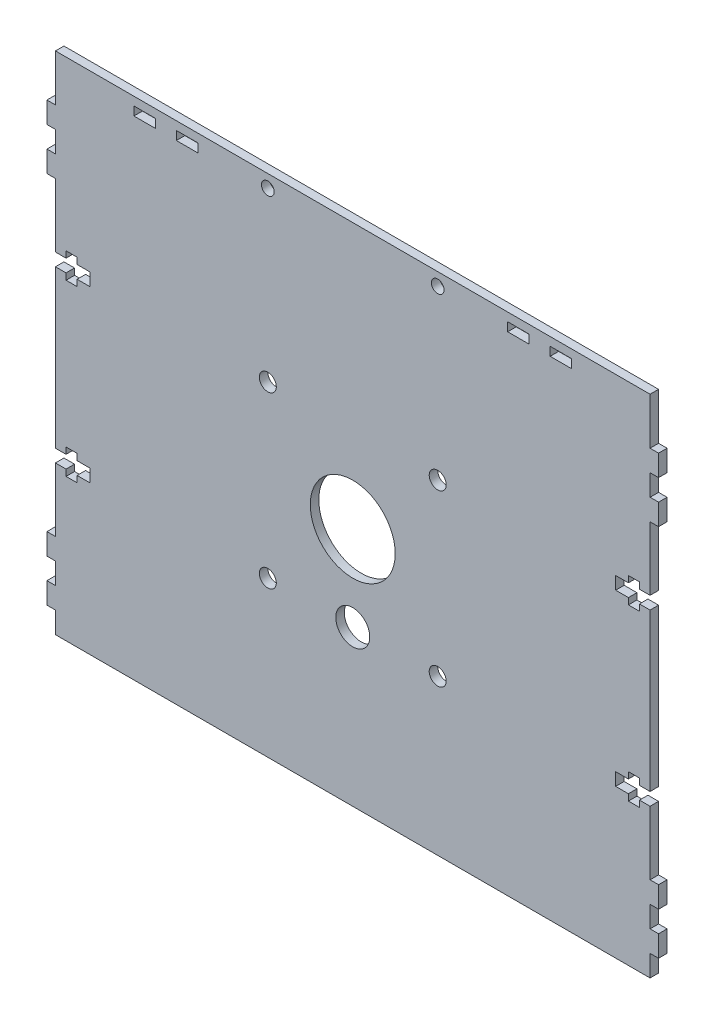
SolidWorks part; units mm, degrees
ref_plane "前视基准面" through (0, 0, 0) normal (0, 0, 1) x (1, 0, 0)
ref_plane "上视基准面" through (0, 0, 0) normal (0, 1, 0) x (1, 0, 0)
ref_plane "右视基准面" through (0, 0, 0) normal (1, 0, 0) x (0, 0, -1)
sketch "草图1" plane through (0, 0, 0) normal (0, 0, 1) x (1, 0, 0)
  line L50 (249.9534, 275.9629) -> (249.9534, 255.9629) construction
  line L53 (317.4534, 257.4629) -> (317.4534, 258.9629)
  line L54 (317.4534, 254.4629) -> (317.4534, 252.9629)
  line L55 (319.9534, 254.4629) -> (317.4534, 254.4629)
  line L56 (317.4534, 258.9629) -> (314.8534, 258.9629)
  line L57 (314.8534, 258.9629) -> (314.8534, 257.4629)
  line L58 (314.8534, 257.4629) -> (311.8534, 257.4629)
  line L59 (311.8534, 254.4629) -> (311.8534, 257.4629)
  line L60 (314.8534, 254.4629) -> (311.8534, 254.4629)
  line L61 (314.8534, 252.9629) -> (314.8534, 254.4629)
  line L62 (317.4534, 252.9629) -> (314.8534, 252.9629)
  line L63 (317.4534, 257.4629) -> (319.9534, 257.4629)
  line L68 (319.9534, 254.4629) -> (319.9534, 257.4629) construction
  line L69 (311.8534, 255.9629) -> (319.9534, 255.9629) construction
  line L73 (311.8534, 295.9629) -> (319.9534, 295.9629) construction
  line L75 (317.4534, 294.4629) -> (319.9534, 294.4629)
  line L76 (317.4534, 298.9629) -> (314.8534, 298.9629)
  line L77 (314.8534, 298.9629) -> (314.8534, 297.4629)
  line L78 (314.8534, 297.4629) -> (311.8534, 297.4629)
  line L79 (311.8534, 297.4629) -> (311.8534, 294.4629)
  line L80 (314.8534, 294.4629) -> (311.8534, 294.4629)
  line L81 (314.8534, 292.9629) -> (314.8534, 294.4629)
  line L82 (317.4534, 292.9629) -> (314.8534, 292.9629)
  line L83 (319.9534, 297.4629) -> (317.4534, 297.4629)
  line L84 (317.4534, 297.4629) -> (317.4534, 298.9629)
  line L85 (317.4534, 294.4629) -> (317.4534, 292.9629)
  line L111 (182.4534, 294.4629) -> (182.4534, 292.9629)
  line L112 (182.4534, 297.4629) -> (182.4534, 298.9629)
  line L113 (179.9534, 297.4629) -> (182.4534, 297.4629)
  line L114 (182.4534, 292.9629) -> (185.0534, 292.9629)
  line L115 (185.0534, 292.9629) -> (185.0534, 294.4629)
  line L116 (185.0534, 294.4629) -> (188.0534, 294.4629)
  line L117 (188.0534, 297.4629) -> (188.0534, 294.4629)
  line L118 (185.0534, 297.4629) -> (188.0534, 297.4629)
  line L119 (185.0534, 298.9629) -> (185.0534, 297.4629)
  line L120 (182.4534, 298.9629) -> (185.0534, 298.9629)
  line L121 (182.4534, 294.4629) -> (179.9534, 294.4629)
  line L122 (182.4534, 257.4629) -> (179.9534, 257.4629)
  line L123 (182.4534, 252.9629) -> (185.0534, 252.9629)
  line L124 (185.0534, 252.9629) -> (185.0534, 254.4629)
  line L125 (185.0534, 254.4629) -> (188.0534, 254.4629)
  line L126 (188.0534, 254.4629) -> (188.0534, 257.4629)
  line L127 (185.0534, 257.4629) -> (188.0534, 257.4629)
  line L128 (185.0534, 258.9629) -> (185.0534, 257.4629)
  line L129 (182.4534, 258.9629) -> (185.0534, 258.9629)
  line L130 (179.9534, 254.4629) -> (182.4534, 254.4629)
  line L131 (182.4534, 254.4629) -> (182.4534, 252.9629)
  line L132 (182.4534, 257.4629) -> (182.4534, 258.9629)
  line L133 (179.9534, 297.4629) -> (179.9534, 294.4629) construction
  line L134 (188.0534, 295.9629) -> (179.9534, 295.9629) construction
  line L135 (188.0534, 255.9629) -> (179.9534, 255.9629) construction
  line L163 (179.9534, 294.4629) -> (179.9534, 257.4629)
  line L172 (319.9534, 257.4629) -> (319.9534, 294.4629)
  line L188 (179.9534, 239.4629) -> (177.9534, 239.4629)
  line L189 (177.9534, 239.4629) -> (177.9534, 234.4629)
  line L190 (177.9534, 234.4629) -> (179.9534, 234.4629)
  line L191 (179.9534, 234.4629) -> (179.9534, 229.4629)
  line L192 (179.9534, 229.4629) -> (177.9534, 229.4629)
  line L193 (177.9534, 229.4629) -> (177.9534, 224.4629)
  line L194 (177.9534, 224.4629) -> (179.9534, 224.4629)
  line L196 (179.9534, 327.4629) -> (179.9534, 345.9629) construction
  line L197 (177.9534, 327.4629) -> (179.9534, 327.4629)
  line L198 (177.9534, 322.4629) -> (177.9534, 327.4629)
  line L199 (179.9534, 322.4629) -> (177.9534, 322.4629)
  line L200 (179.9534, 317.4629) -> (179.9534, 322.4629)
  line L201 (177.9534, 317.4629) -> (179.9534, 317.4629)
  line L202 (177.9534, 312.4629) -> (177.9534, 317.4629)
  line L203 (179.9534, 312.4629) -> (177.9534, 312.4629)
  line L224 (319.9534, 312.4629) -> (321.9534, 312.4629)
  line L225 (321.9534, 312.4629) -> (321.9534, 317.4629)
  line L226 (321.9534, 317.4629) -> (319.9534, 317.4629)
  line L227 (319.9534, 317.4629) -> (319.9534, 322.4629)
  line L228 (319.9534, 322.4629) -> (321.9534, 322.4629)
  line L229 (321.9534, 322.4629) -> (321.9534, 327.4629)
  line L230 (321.9534, 327.4629) -> (319.9534, 327.4629)
  line L233 (321.9534, 224.4629) -> (319.9534, 224.4629)
  line L234 (321.9534, 229.4629) -> (321.9534, 224.4629)
  line L235 (319.9534, 229.4629) -> (321.9534, 229.4629)
  line L236 (319.9534, 234.4629) -> (319.9534, 229.4629)
  line L237 (321.9534, 234.4629) -> (319.9534, 234.4629)
  line L238 (321.9534, 239.4629) -> (321.9534, 234.4629)
  line L239 (319.9534, 239.4629) -> (321.9534, 239.4629)
  line L261 (249.9534, 255.9629) -> (229.9534, 255.9629) construction
  line L262 (319.9534, 327.4629) -> (319.9534, 330.9829)
  line L268 (179.9534, 297.4629) -> (179.9534, 312.4629)
  line L271 (319.9534, 312.4629) -> (319.9534, 297.4629)
  line L272 (319.9534, 254.4629) -> (319.9534, 239.4629)
  line L275 (179.9534, 239.4629) -> (179.9534, 254.4629)
  line L279 (317.4534, 330.9829) -> (317.4534, 345.9629) construction
  line L280 (317.4534, 345.9629) -> (179.9534, 345.9629) construction
  line L285 (317.4534, 338.4729) -> (179.9534, 338.4729)
  line L286 (179.9534, 327.4629) -> (179.9534, 338.4729)
  line L288 (317.4534, 338.4729) -> (319.9534, 338.4729)
  line L289 (319.9534, 338.4729) -> (319.9534, 330.9829)
  line L290 (319.9534, 219.4409) -> (179.9534, 219.4409)
  line L291 (179.9534, 219.4409) -> (179.9534, 224.4629)
  line L292 (319.9534, 219.4409) -> (319.9534, 224.4629)
  line L310 (203.4784, 334.4379) -> (198.4284, 336.4879) construction
  line L311 (286.4284, 336.4879) -> (291.4784, 336.4879)
  line L312 (286.4284, 336.4879) -> (286.4284, 334.4379)
  line L313 (286.4284, 334.4379) -> (291.4784, 334.4379)
  line L314 (291.4784, 336.4879) -> (291.4784, 334.4379)
  line L315 (286.4284, 336.4879) -> (291.4784, 334.4379) construction
  line L316 (286.4284, 334.4379) -> (291.4784, 336.4879) construction
  line L317 (296.4284, 336.4879) -> (301.4784, 336.4879)
  line L318 (296.4284, 336.4879) -> (296.4284, 334.4379)
  line L319 (296.4284, 334.4379) -> (301.4784, 334.4379)
  line L320 (301.4784, 336.4879) -> (301.4784, 334.4379)
  line L321 (296.4284, 336.4879) -> (301.4784, 334.4379) construction
  line L322 (296.4284, 334.4379) -> (301.4784, 336.4879) construction
  line L323 (268.4534, 343.4629) -> (266.9534, 343.4629) [skipped]
  line L324 (271.4534, 343.4629) -> (272.9534, 343.4629) [skipped]
  line L325 (271.4534, 345.9629) -> (271.4534, 343.4629) [skipped]
  line L326 (266.9534, 343.4629) -> (266.9534, 340.8629) [skipped]
  line L327 (266.9534, 340.8629) -> (268.4534, 340.8629) [skipped]
  line L328 (268.4534, 340.8629) -> (268.4534, 337.8629) [skipped]
  line L329 (271.4534, 340.8629) -> (271.4534, 337.8629) [skipped]
  line L330 (272.9534, 340.8629) -> (271.4534, 340.8629) [skipped]
  line L331 (272.9534, 343.4629) -> (272.9534, 340.8629) [skipped]
  line L332 (268.4534, 343.4629) -> (268.4534, 345.9629) [skipped]
  line L333 (231.4534, 343.4629) -> (231.4534, 345.9629) [skipped]
  line L334 (226.9534, 343.4629) -> (226.9534, 340.8629) [skipped]
  line L335 (226.9534, 340.8629) -> (228.4534, 340.8629) [skipped]
  line L336 (228.4534, 340.8629) -> (228.4534, 337.8629) [skipped]
  line L337 (231.4534, 340.8629) -> (231.4534, 337.8629) [skipped]
  line L338 (232.9534, 340.8629) -> (231.4534, 340.8629) [skipped]
  line L339 (232.9534, 343.4629) -> (232.9534, 340.8629) [skipped]
  line L340 (228.4534, 345.9629) -> (228.4534, 343.4629) [skipped]
  line L341 (228.4534, 343.4629) -> (226.9534, 343.4629) [skipped]
  line L342 (231.4534, 343.4629) -> (232.9534, 343.4629) [skipped]
  line L343 (268.4534, 345.9629) -> (231.4534, 345.9629) [skipped]
  line L344 (213.4534, 345.9629) -> (213.4534, 347.9629) [skipped]
  line L345 (213.4534, 347.9629) -> (208.4534, 347.9629) [skipped]
  line L346 (208.4534, 347.9629) -> (208.4534, 345.9629) [skipped]
  line L347 (208.4534, 345.9629) -> (203.4534, 345.9629) [skipped]
  line L348 (203.4534, 345.9629) -> (203.4534, 347.9629) [skipped]
  line L349 (203.4534, 347.9629) -> (198.4534, 347.9629) [skipped]
  line L350 (198.4534, 347.9629) -> (198.4534, 345.9629) [skipped]
  line L352 (301.4534, 345.9629) -> (319.9534, 345.9629) [skipped]
  line L353 (301.4534, 347.9629) -> (301.4534, 345.9629) [skipped]
  line L354 (296.4534, 347.9629) -> (301.4534, 347.9629) [skipped]
  line L355 (296.4534, 345.9629) -> (296.4534, 347.9629) [skipped]
  line L356 (291.4534, 345.9629) -> (296.4534, 345.9629) [skipped]
  line L357 (291.4534, 347.9629) -> (291.4534, 345.9629) [skipped]
  line L358 (286.4534, 347.9629) -> (291.4534, 347.9629) [skipped]
  line L359 (286.4534, 345.9629) -> (286.4534, 347.9629) [skipped]
  line L360 (271.4534, 345.9629) -> (268.4534, 345.9629) construction
  line L361 (269.9534, 337.8629) -> (269.9534, 345.9629) construction
  line L362 (229.9534, 337.8629) -> (229.9534, 345.9629) construction
  line L363 (271.4534, 337.8629) -> (268.4534, 337.8629) [skipped]
  line L364 (228.4534, 337.8629) -> (231.4534, 337.8629) [skipped]
  line L365 (203.4784, 336.4879) -> (198.4284, 334.4379) construction
  line L366 (213.4784, 334.4379) -> (208.4284, 336.4879) construction
  line L367 (213.4784, 336.4879) -> (208.4284, 334.4379) construction
  line L368 (198.4284, 336.4879) -> (198.4284, 334.4379)
  line L369 (203.4784, 334.4379) -> (198.4284, 334.4379)
  line L370 (203.4784, 336.4879) -> (203.4784, 334.4379)
  line L371 (203.4784, 336.4879) -> (198.4284, 336.4879)
  line L372 (208.4284, 336.4879) -> (208.4284, 334.4379)
  line L373 (213.4784, 334.4379) -> (208.4284, 334.4379)
  line L374 (213.4784, 336.4879) -> (213.4784, 334.4379)
  line L375 (213.4784, 336.4879) -> (208.4284, 336.4879)
  line L377 (231.4534, 208.4629) -> (232.9534, 208.4629) [skipped]
  line L378 (228.4534, 208.4629) -> (226.9534, 208.4629) [skipped]
  line L379 (228.4534, 205.9629) -> (228.4534, 208.4629) [skipped]
  line L380 (232.9534, 208.4629) -> (232.9534, 211.0629) [skipped]
  line L381 (232.9534, 211.0629) -> (231.4534, 211.0629) [skipped]
  line L382 (231.4534, 211.0629) -> (231.4534, 214.0629) [skipped]
  line L383 (228.4534, 214.0629) -> (231.4534, 214.0629) [skipped]
  line L384 (228.4534, 211.0629) -> (228.4534, 214.0629) [skipped]
  line L385 (226.9534, 211.0629) -> (228.4534, 211.0629) [skipped]
  line L386 (226.9534, 208.4629) -> (226.9534, 211.0629) [skipped]
  line L387 (231.4534, 208.4629) -> (231.4534, 205.9629) [skipped]
  line L388 (268.4534, 208.4629) -> (268.4534, 205.9629) [skipped]
  line L389 (272.9534, 208.4629) -> (272.9534, 211.0629) [skipped]
  line L390 (272.9534, 211.0629) -> (271.4534, 211.0629) [skipped]
  line L391 (271.4534, 211.0629) -> (271.4534, 214.0629) [skipped]
  line L392 (271.4534, 214.0629) -> (268.4534, 214.0629) [skipped]
  line L393 (268.4534, 211.0629) -> (268.4534, 214.0629) [skipped]
  line L394 (266.9534, 211.0629) -> (268.4534, 211.0629) [skipped]
  line L395 (266.9534, 208.4629) -> (266.9534, 211.0629) [skipped]
  line L396 (271.4534, 205.9629) -> (271.4534, 208.4629) [skipped]
  line L397 (271.4534, 208.4629) -> (272.9534, 208.4629) [skipped]
  line L398 (268.4534, 208.4629) -> (266.9534, 208.4629) [skipped]
  line L399 (231.4534, 205.9629) -> (268.4534, 205.9629) [skipped]
  line L400 (286.4534, 205.9629) -> (286.4534, 203.9629) [skipped]
  line L401 (286.4534, 203.9629) -> (291.4534, 203.9629) [skipped]
  line L402 (291.4534, 203.9629) -> (291.4534, 205.9629) [skipped]
  line L403 (291.4534, 205.9629) -> (296.4534, 205.9629) [skipped]
  line L404 (296.4534, 205.9629) -> (296.4534, 203.9629) [skipped]
  line L405 (296.4534, 203.9629) -> (301.4534, 203.9629) [skipped]
  line L406 (301.4534, 203.9629) -> (301.4534, 205.9629) [skipped]
  line L408 (198.4534, 205.9629) -> (179.9534, 205.9629) [skipped]
  line L409 (198.4534, 203.9629) -> (198.4534, 205.9629) [skipped]
  line L410 (203.4534, 203.9629) -> (198.4534, 203.9629) [skipped]
  line L411 (203.4534, 205.9629) -> (203.4534, 203.9629) [skipped]
  line L412 (208.4534, 205.9629) -> (203.4534, 205.9629) [skipped]
  line L413 (208.4534, 203.9629) -> (208.4534, 205.9629) [skipped]
  line L414 (213.4534, 203.9629) -> (208.4534, 203.9629) [skipped]
  line L415 (213.4534, 205.9629) -> (213.4534, 203.9629) [skipped]
  line L416 (228.4534, 205.9629) -> (231.4534, 205.9629) construction
  line L417 (229.9534, 214.0629) -> (229.9534, 205.9629) construction
  line L418 (269.9534, 214.0629) -> (269.9534, 205.9629) construction
  line L419 (319.9534, 224.4629) -> (319.9534, 205.9629) [skipped]
  circle A14 centre (249.9534, 275.9629) radius 10
  circle A24 centre (249.9534, 255.9629) radius 4
  circle A27 centre (229.9534, 335.4629) radius 1.5
  circle A28 centre (269.9534, 335.4629) radius 1.5
  circle A29 centre (229.9534, 255.9629) radius 2
  circle A30 centre (229.9534, 295.9629) radius 2
  circle A31 centre (269.9534, 295.9629) radius 2
  circle A32 centre (269.9534, 255.9629) radius 2
  point P107 (210.9534, 335.4629)
  point P232 (288.9534, 335.4629)
  dimension "D1" = 7.49
  dimension "D5" = 4
  dimension "D4" = 4
extrude "凸台-拉伸1" add sketch "草图1" along normal blind 2
sketch "草图2" plane through (179.9534, 0, 0) normal (-1, 0, 0) x (0, 0, 1)
  line L0 (1, 294.4629) -> (1, 297.4629) construction
  line L1 (2, 294.4629) -> (0, 294.4629) construction
  line L2 (2, 297.4629) -> (0, 297.4629) construction
  line L3 (1, 295.9629) -> (1, 312.4629) construction
  line L4 (2, 312.4629) -> (0, 312.4629) construction
  circle A0 centre (1, 295.9629) radius 1.5
sketch "草图4" plane through (319.9534, 0, 0) normal (1, 0, 0) x (0, 0, -1)
  line L0 (-1, 257.4629) -> (-1, 254.4629) construction
  line L1 (-2, 257.4629) -> (0, 257.4629) construction
  line L2 (-2, 254.4629) -> (0, 254.4629) construction
  circle A0 centre (-1, 255.9629) radius 1.5
